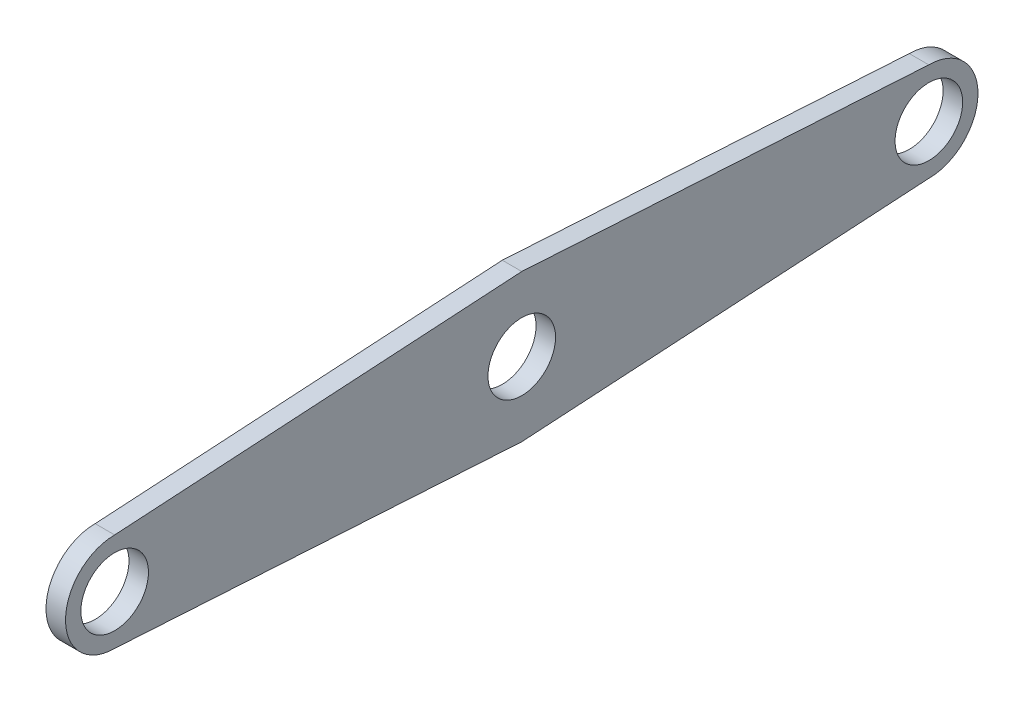
SolidWorks part; units mm, degrees
material "Balsa"
ref_plane "Front Plane" through (0, 0, 0) normal (0, 0, 1) x (1, 0, 0)
ref_plane "Top Plane" through (0, 0, 0) normal (0, 1, 0) x (1, 0, 0)
ref_plane "Right Plane" through (0, 0, 0) normal (1, 0, 0) x (0, 0, -1)
sketch "Sketch1" plane through (0, 0, 0) normal (1, 0, 0) x (0, 0, -1)
  line L0 (0, 0) -> (121.5, 0) construction
  line L3 (0, 16) -> (132.5, 24)
  line L4 (132.5, 24) -> (265, 16)
  line L5 (0, -16) -> (132.5, -24)
  line L6 (132.5, -24) -> (265, -16)
  line L7 (143.5, 0) -> (265, 0) construction
  circle A0 centre (0, 0) radius 11
  circle A1 centre (265, 0) radius 11
  arc A2 (0, 16) -> (0, -16) centre (0, 0) ccw
  arc A3 (265, -16) -> (265, 16) centre (265, 0) ccw
  circle A4 centre (132.5, 0) radius 11
  arc A5 (135.3876, 23.8257) -> (129.6124, 23.8257) centre (132.5, 0) ccw
  arc A6 (129.6124, -23.8257) -> (135.3876, -23.8257) centre (132.5, 0) ccw
extrude "Boss-Extrude1" add sketch "Sketch1" along normal blind 6.35
